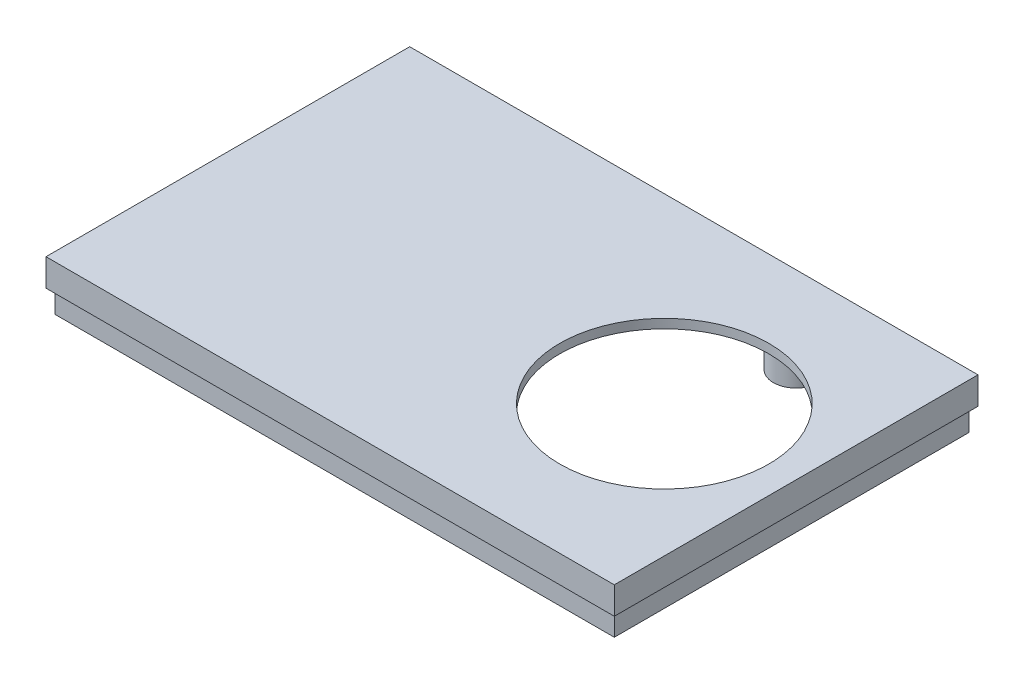
SolidWorks part; units mm, degrees
ref_plane "Front" through (0, 0, 0) normal (0, 0, 1) x (1, 0, 0)
ref_plane "Top" through (0, 0, 0) normal (0, 1, 0) x (1, 0, 0)
ref_plane "Right" through (0, 0, 0) normal (1, 0, 0) x (0, 0, -1)
sketch "Эскиз1" plane through (0, 0, 0) normal (0, 1, 0) x (1, 0, 0)
  line L1 (-39.2791, 6.6512) -> (22.2209, 6.6512)
  line L2 (-39.2791, 6.6512) -> (-39.2791, -32.3488)
  line L3 (-39.2791, -32.3488) -> (22.2209, -32.3488)
  line L4 (22.2209, 6.6512) -> (22.2209, -32.3488)
  dimension "D1" = 61.5
  dimension "D2" = 39
extrude "Бобышка-Вытянуть1" add sketch "Эскиз1" along normal blind 5.5
sketch "Эскиз2" plane through (-39.2791, 0, 0) normal (-1, 0, 0) x (0, 0, 1)
  line L0 (32.3488, 5.5) -> (32.3488, 0) construction
  line L1 (-6.6512, 5.5) -> (32.3488, 5.5)
  line L2 (-6.6512, 5.5) -> (-6.6512, 2.5)
  line L3 (-6.6512, 2.5) -> (32.3488, 2.5)
  line L4 (32.3488, 5.5) -> (32.3488, 2.5)
  dimension "D1" = 3
extrude "Бобышка-Вытянуть2" add sketch "Эскиз2" along normal blind 0.5
sketch "Эскиз3" plane through (0, 0, 32.3488) normal (0, 0, 1) x (1, 0, 0)
  line L0 (-39.7791, 5.5) -> (22.2209, 5.5) construction
  line L1 (-39.7791, 5.5) -> (22.2209, 5.5)
  line L2 (-39.7791, 5.5) -> (-39.7791, 2.5)
  line L3 (-39.7791, 2.5) -> (22.2209, 2.5)
  line L4 (22.2209, 5.5) -> (22.2209, 2.5)
  line L5 (-39.7791, 2.5) -> (-39.7791, 5.5) construction
  line L6 (22.2209, 5.5) -> (22.2209, 0) construction
  dimension "D1" = 3
extrude "Бобышка-Вытянуть3" add sketch "Эскиз3" along normal blind 0.5
sketch "Эскиз5" plane through (22.2209, 0, 0) normal (1, 0, 0) x (0, 0, -1)
  line L1 (-32.8488, 5.5) -> (6.6512, 5.5)
  line L2 (-32.8488, 5.5) -> (-32.8488, 2.5)
  line L3 (-32.8488, 2.5) -> (6.6512, 2.5)
  line L4 (6.6512, 5.5) -> (6.6512, 2.5)
extrude "Бобышка-Вытянуть4" add sketch "Эскиз5" along normal blind 0.5
sketch "Эскиз6" plane through (0, 0, -6.6512) normal (0, 0, -1) x (-1, 0, 0)
  line L1 (-22.7209, 5.5) -> (39.7791, 5.5)
  line L2 (-22.7209, 5.5) -> (-22.7209, 2.5)
  line L3 (-22.7209, 2.5) -> (39.7791, 2.5)
  line L4 (39.7791, 5.5) -> (39.7791, 2.5)
extrude "Бобышка-Вытянуть5" add sketch "Эскиз6" along normal blind 0.5
sketch "Эскиз7" plane through (0, 0, 0) normal (0, -1, 0) x (1, 0, 0)
  line L0 (-39.2791, 32.3488) -> (22.2209, 32.3488) construction
  line L1 (-38.7791, 31.8488) -> (21.7209, 31.8488)
  line L2 (-38.7791, 31.8488) -> (-38.7791, -6.1512)
  line L3 (-38.7791, -6.1512) -> (21.7209, -6.1512)
  line L4 (21.7209, 31.8488) -> (21.7209, -6.1512)
  line L5 (22.2209, -6.6512) -> (-39.2791, -6.6512) construction
  line L6 (-39.2791, -6.6512) -> (-39.2791, 32.3488) construction
  line L7 (22.2209, 32.3488) -> (22.2209, -6.6512) construction
  dimension "D1" = 0.5
  dimension "D2" = 0.5
  dimension "D3" = 0.5
  dimension "D4" = 0.5
extrude "Вырез-Вытянуть1" cut sketch "Эскиз7" against normal blind 4.5
sketch "Эскиз8" plane through (0, 5.5, 0) normal (0, 1, 0) x (1, 0, 0)
  line L7 (22.7209, 7.1512) -> (22.7209, -32.8488) construction
  circle A0 centre (8.2209, -12.8488) radius 11.5
  dimension "D1" = 14.5
extrude "Вырез-Вытянуть2" cut sketch "Эскиз8" against normal blind 12
sketch "Эскиз9" plane through (0, 5.5, 0) normal (0, 1, 0) x (1, 0, 0)
  line L0 (22.7209, 7.1512) -> (22.7209, -32.8488) construction
  line L1 (-4.2791, 3.6512) -> (20.7209, 3.6512)
  line L2 (-4.2791, 3.6512) -> (-4.2791, -29.3488)
  line L3 (-4.2791, -29.3488) -> (20.7209, -29.3488)
  line L4 (20.7209, 3.6512) -> (20.7209, -29.3488)
  line L5 (-39.7791, 7.1512) -> (22.7209, 7.1512) construction
  circle A0 centre (8.2209, 1.6512) radius 2.5
  circle A1 centre (8.2209, -12.8488) radius 11.5 construction
  circle A2 centre (8.2209, -27.3488) radius 2.5
  dimension "D5" = 14.5
  dimension "D6" = 14.5
  dimension "D7" = 5
  dimension "D1" = 33
  dimension "D2" = 25
  dimension "D3" = 2
  dimension "D4" = 3.5
  dimension "D8" = 12.5
  dimension "D9" = 12.5
extrude "Бобышка-Вытянуть7" add sketch "Эскиз9" against normal blind 4 contours A2 | A0
sketch "Эскиз10" plane through (0, 1.5, 0) normal (0, -1, 0) x (1, 0, 0)
  circle A0 centre (8.2209, -1.6512) radius 1.0032
  circle A1 centre (8.2209, 27.3488) radius 1
extrude "Вырез-Вытянуть3" cut sketch "Эскиз10" against normal blind 3
